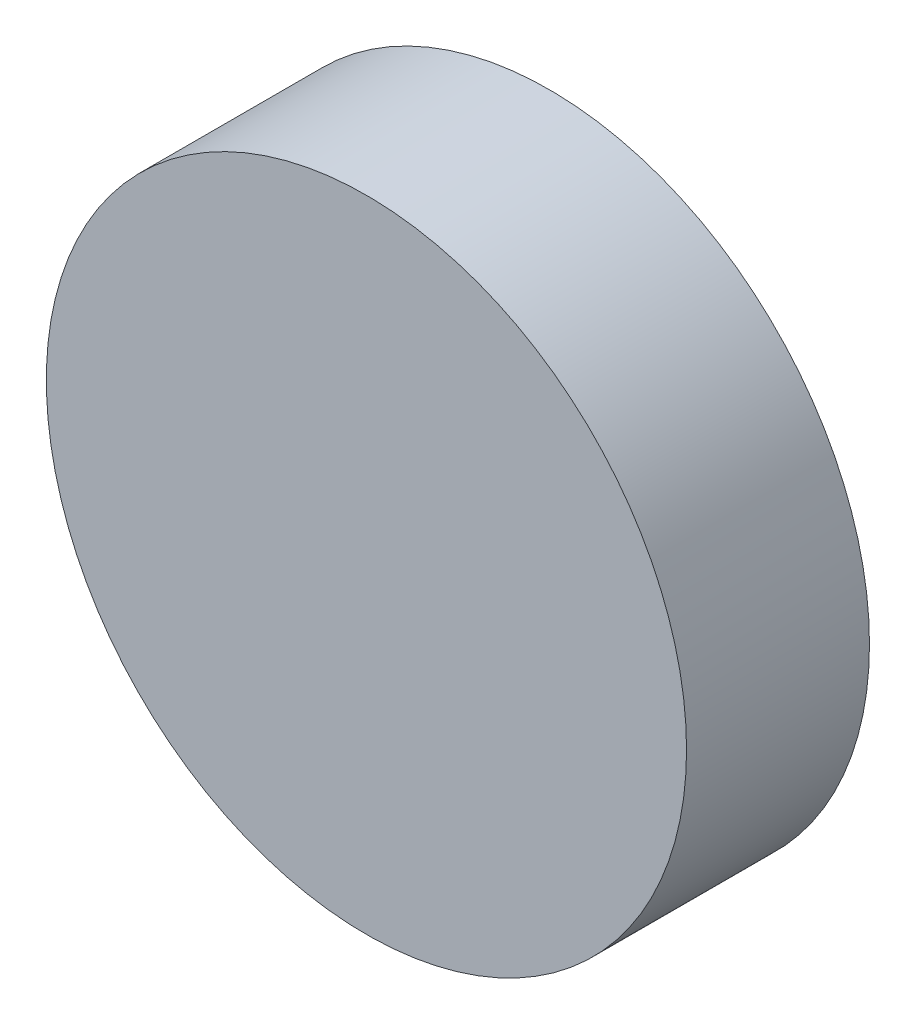
SolidWorks part; units mm, degrees
ref_plane "Front Plane" through (0, 0, 0) normal (0, 0, 1) x (1, 0, 0)
ref_plane "Top Plane" through (0, 0, 0) normal (0, 1, 0) x (1, 0, 0)
ref_plane "Right Plane" through (0, 0, 0) normal (1, 0, 0) x (0, 0, -1)
sketch "Sketch1" plane through (0, 0, 0) normal (0, 0, 1) x (1, 0, 0)
  circle A0 centre (0, 0) radius 17.5
extrude "Boss-Extrude1" add sketch "Sketch1" along normal blind 10
